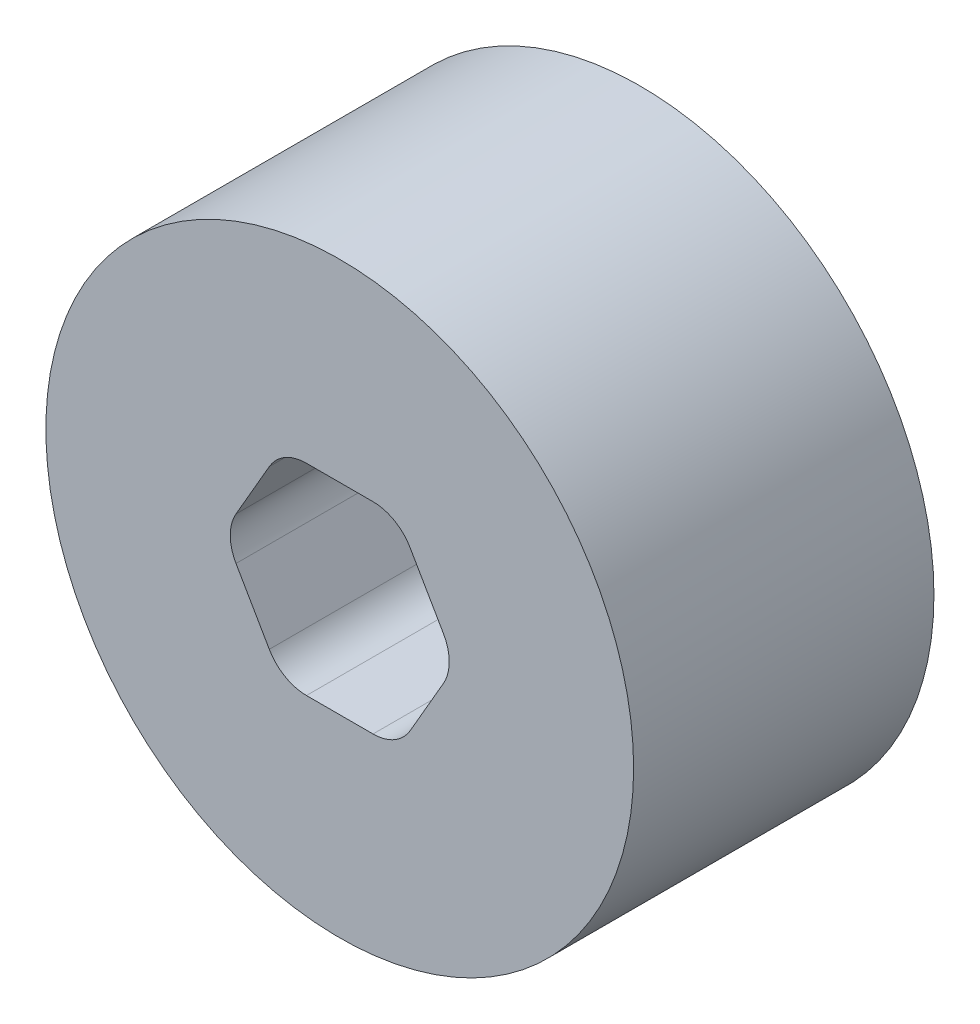
SolidWorks part; units mm, degrees
material "Alloy Steel"
ref_plane "Front Plane" through (0, 0, 0) normal (0, 0, 1) x (1, 0, 0)
ref_plane "Top Plane" through (0, 0, 0) normal (0, 1, 0) x (1, 0, 0)
ref_plane "Right Plane" through (0, 0, 0) normal (1, 0, 0) x (0, 0, -1)
sketch "Sketch1" plane through (0, 0, 0) normal (0, 0, 1) x (1, 0, 0)
  line L1 (6.8758, 0) -> (3.4379, 5.9546)
  line L2 (3.4379, 5.9546) -> (-3.4379, 5.9546)
  line L3 (-3.4379, 5.9546) -> (-6.8758, 0)
  line L4 (-6.8758, 0) -> (-3.4379, -5.9546)
  line L5 (-3.4379, -5.9546) -> (3.4379, -5.9546)
  line L6 (3.4379, -5.9546) -> (6.8758, 0)
  circle A9 centre (0, 0) radius 17.399
  dimension "D1" = 34.798
  dimension "D2" = 6.8758
  dimension "D3" = 5.9546
  dimension "D4" = 5.9546
extrude "Boss-Extrude1" add sketch "Sketch1" along normal blind 17.78
fillet "Fillet1" radius 2.54 6 edges at (3.4379, 5.9546, 8.89) (6.8758, 0, 8.89) (-3.4379, 5.9546, 8.89) (-6.8758, 0, 8.89) (-3.4379, -5.9546, 8.89) (3.4379, -5.9546, 8.89)
